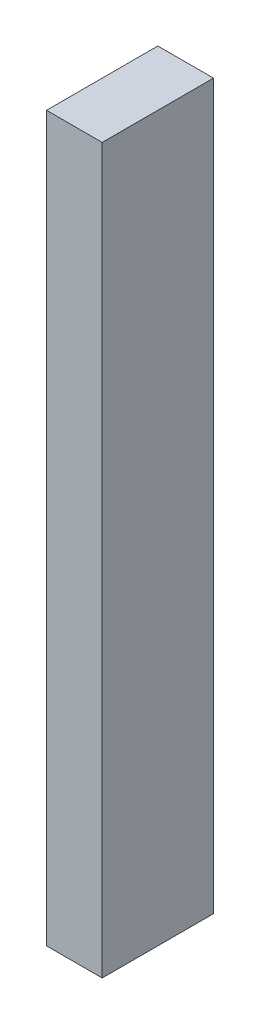
SolidWorks part; units mm, degrees
ref_plane "Front Plane" through (0, 0, 0) normal (0, 0, 1) x (1, 0, 0)
ref_plane "Top Plane" through (0, 0, 0) normal (0, 1, 0) x (1, 0, 0)
ref_plane "Right Plane" through (0, 0, 0) normal (1, 0, 0) x (0, 0, -1)
sketch "Sketch1" plane through (0, 0, 0) normal (0, 1, 0) x (1, 0, 0)
  line L1 (20, -40) -> (-20, -40)
  line L2 (20, -40) -> (20, 40)
  line L3 (20, 40) -> (-20, 40)
  line L4 (-20, -40) -> (-20, 40)
  line L5 (20, -40) -> (-20, 40) construction
  line L6 (20, 40) -> (-20, -40) construction
  point P0 (0, 0)
  dimension "D1" = 40
  dimension "D2" = 80
extrude "Boss-Extrude1" add sketch "Sketch1" along normal blind 520
